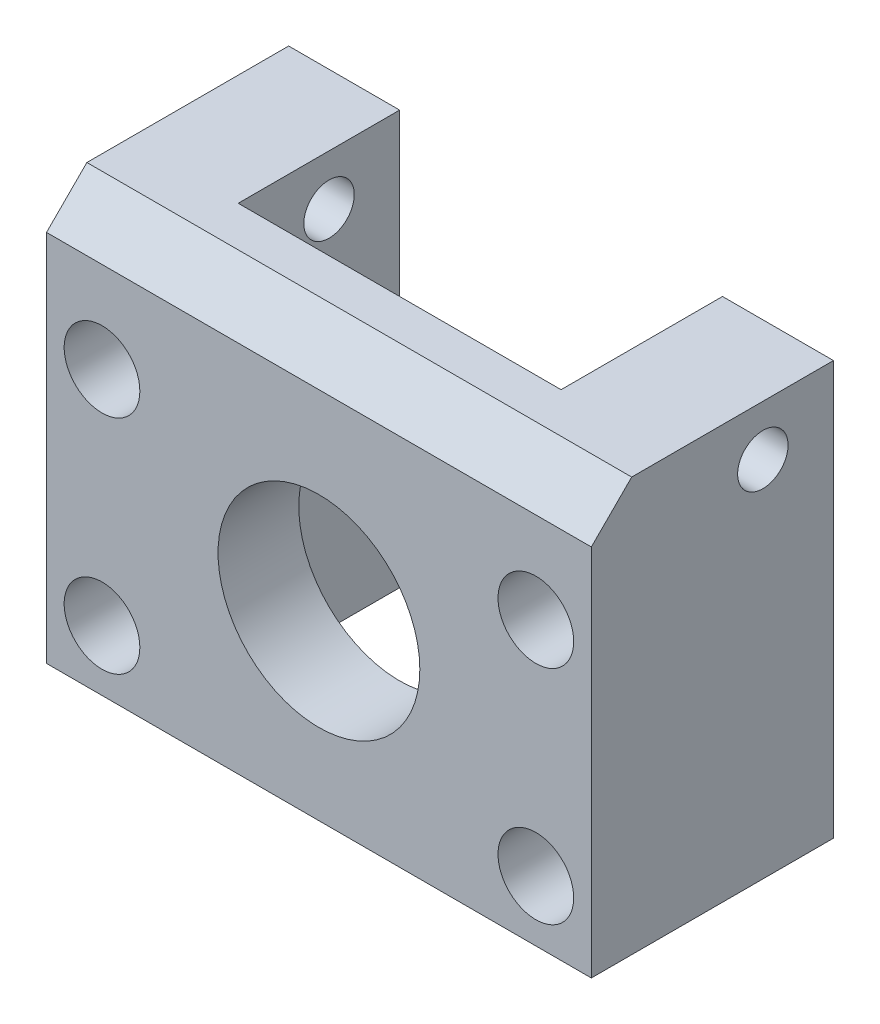
SolidWorks part; units mm, degrees
ref_plane "Alzado" through (0, 0, 0) normal (0, 0, 1) x (1, 0, 0)
ref_plane "Planta" through (0, 0, 0) normal (0, 1, 0) x (1, 0, 0)
ref_plane "Vista lateral" through (0, 0, 0) normal (1, 0, 0) x (0, 0, -1)
sketch "Croquis1" plane through (0, 0, 0) normal (0, 0, 1) x (1, 0, 0)
  line L1 (-27, 20.5) -> (27, 20.5)
  line L2 (-27, 20.5) -> (-27, -20.5)
  line L3 (-27, -20.5) -> (27, -20.5)
  line L4 (27, 20.5) -> (27, -20.5)
  line L5 (-27, 20.5) -> (27, -20.5) construction
  line L6 (-27, -20.5) -> (27, 20.5) construction
  circle A0 centre (-21.5, 7.5) radius 3.75
  circle A1 centre (21.5, 7.5) radius 3.75
  circle A2 centre (21.5, -14.5) radius 3.75
  circle A3 centre (-21.5, -14.5) radius 3.75
  point P0 (0, 0)
  dimension "D3" = 21.5
  dimension "D6" = 21.5
  dimension "D7" = 22
  dimension "D8" = 13
  dimension "D9" = 22
  dimension "D10" = 13
  dimension "D11" = 7.5
  dimension "D12" = 7.5
  dimension "D13" = 7.5
  dimension "D14" = 7.5
  dimension "D1" = 54
  dimension "D2" = 41
  dimension "D4" = 21.5
  dimension "D5" = 21.5
extrude "Saliente-Extruir1" add sketch "Croquis1" against normal blind 24
sketch "Croquis2" plane through (0, 0, -24) normal (0, 0, -1) x (-1, 0, 0)
  line L0 (27, -20.5) -> (-27, -20.5) construction
  line L1 (-16, 20.5) -> (16, 20.5)
  line L2 (-16, 20.5) -> (-16, -20.5)
  line L3 (-16, -20.5) -> (16, -20.5)
  line L4 (16, 20.5) -> (16, -20.5)
  line L5 (-16, 20.5) -> (16, -20.5) construction
  line L6 (-16, -20.5) -> (16, 20.5) construction
  point P0 (0, 0)
  dimension "D1" = 32
extrude "Cortar-Extruir1" cut sketch "Croquis2" against normal blind 16
sketch "Croquis3" plane through (27, 0, 0) normal (1, 0, 0) x (0, 0, -1)
  line L0 (24, 20.5) -> (0, 20.5) construction
  line L1 (24, -20.5) -> (24, 20.5) construction
  circle A0 centre (17, 15.5) radius 2.5
  dimension "D1" = 5
  dimension "D2" = 7
  dimension "D3" = 5
extrude "Cortar-Extruir2" cut sketch "Croquis3" against normal through all
chamfer "Chaflán1" distance 4 angle 45 1 edges at (0, 20.5, 0)
sketch "Croquis4" plane through (0, 0, 0) normal (0, 0, 1) x (1, 0, 0)
  line L0 (-27, 20.5) -> (27, 20.5) construction
  circle A0 centre (0, -2.5) radius 10
  dimension "D1" = 23
  dimension "D2" = 20
extrude "Cortar-Extruir3" cut sketch "Croquis4" against normal up to next
